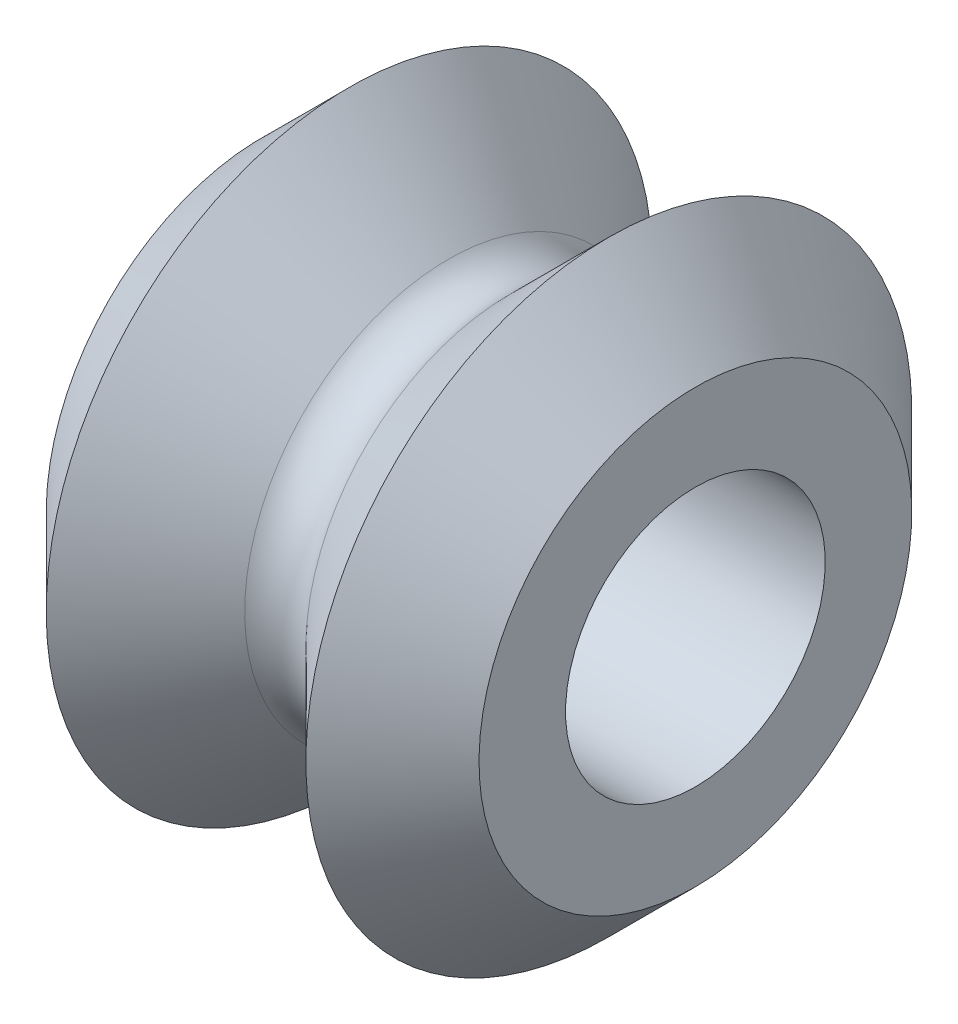
SolidWorks part; units mm, degrees
ref_plane "Front Plane" through (0, 0, 0) normal (0, 0, 1) x (1, 0, 0)
ref_plane "Top Plane" through (0, 0, 0) normal (0, 1, 0) x (1, 0, 0)
ref_plane "Right Plane" through (0, 0, 0) normal (1, 0, 0) x (0, 0, -1)
sketch "Sketch1" plane through (0, 0, 0) normal (0, 0, 1) x (1, 0, 0)
  line L0 (5, 0) -> (5, 5)
  line L1 (55, 0) -> (-55, 0) construction
  line L2 (5, 5) -> (3, 7)
  line L3 (3, 7) -> (0, 4)
  line L4 (0, -55) -> (0, 55) construction
  line L5 (0, 4) -> (-3, 7)
  line L6 (-3, 7) -> (-5, 5)
  line L7 (-5, 5) -> (-5, 0)
  line L8 (-5, 0) -> (5, 0)
  line L9 (0, 27.0331) -> (0, -8.4941) construction
  dimension "D1" = 5
  dimension "D2" = 5
  dimension "D3" = 10
  dimension "D4" = 2
  dimension "D5" = 2
revolve "Revolve1" add sketch "Sketch1" angle 360 about L8
fillet "Fillet1" radius 1 1 edges at (0, -4, 0)
sketch "Sketch2" plane through (5, 0, 0) normal (1, 0, 0) x (0, 0, -1)
  circle A0 centre (0, 0) radius 3
  dimension "D1" = 6
extrude "Cut-Extrude1" cut sketch "Sketch2" against normal through all
